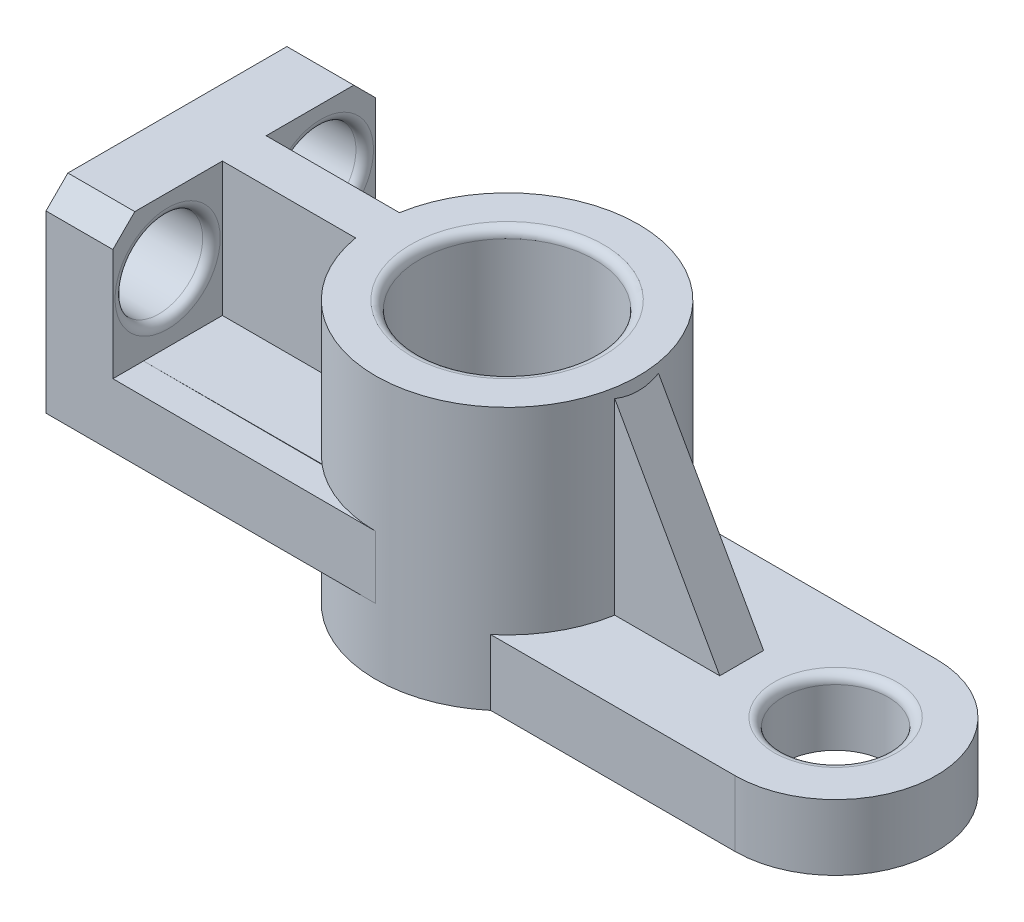
SolidWorks part; units mm, degrees
ref_plane "Front Plane" through (0, 0, 0) normal (0, 0, 1) x (1, 0, 0)
ref_plane "Top Plane" through (0, 0, 0) normal (0, 1, 0) x (1, 0, 0)
ref_plane "Right Plane" through (0, 0, 0) normal (1, 0, 0) x (0, 0, -1)
sketch "Sketch1" plane through (0, 0, 0) normal (0, 1, 0) x (1, 0, 0)
  circle A0 centre (0, 14.6047) radius 30
  circle A1 centre (0, 14.6047) radius 20
  dimension "D1" = 60
extrude "Boss-Extrude1" add sketch "Sketch1" along normal blind 60
fillet "Fillet1" radius 2 1 edges at (0, 60, 5.3953)
sketch "Sketch2" plane through (0, 0, 0) normal (0, 1, 0) x (1, 0, 0)
  line L0 (19.2614, 37.6047) -> (19.2614, -8.3953)
  line L1 (19.2614, 14.6047) -> (75, 14.6047) construction
  line L2 (19.2614, 37.6047) -> (75, 37.6047)
  line L3 (19.2614, -8.3953) -> (75, -8.3953)
  line L4 (0, 44.6047) -> (0, -15.3953) construction
  circle A0 centre (0, 14.6047) radius 30 construction
  arc A1 (19.2614, 37.6047) -> (19.2614, -8.3953) centre (19.2614, 14.6047) ccw
  arc A2 (75, -8.3953) -> (75, 37.6047) centre (75, 14.6047) ccw
  circle A3 centre (75, 14.6047) radius 12
  point P6 (47.1307, 14.6047)
  dimension "D3" = 75
  dimension "D2" = 23
  dimension "D1" = 46
extrude "Boss-Extrude2" add sketch "Sketch2" along normal blind 15
sketch "Sketch3" plane through (0, 0, 8.3953) normal (0, 0, 1) x (1, 0, 0)
  line L0 (19.2614, 0) -> (19.2614, 15)
  line L1 (0, 15) -> (-60, 15)
  line L2 (0, 15) -> (0, 29.461)
  line L3 (0, 29.461) -> (-60, 29.461)
  line L4 (-60, 29.461) -> (-60, 15)
  dimension "D1" = 60
extrude "Boss-Extrude3" add sketch "Sketch3" against normal blind 46 contours L3 L4 L1 L2
sketch "Sketch4" plane through (0, 0, 8.3953) normal (0, 0, 1) x (1, 0, 0)
  line L0 (-60, 29.461) -> (-60, 60)
  line L1 (-60, 60) -> (-75.2694, 60)
  line L2 (-75.2694, 60) -> (-75.2694, 15)
  line L3 (-75.2694, 15) -> (-60, 15)
  line L4 (-60, 29.461) -> (-60, 15)
  dimension "D1" = 45
extrude "Boss-Extrude4" add sketch "Sketch4" against normal blind 46
sketch "Sketch5" plane through (0, 60, 0) normal (0, 1, 0) x (1, 0, 0)
  line L0 (-30, 14.6047) -> (-60, 14.6047) construction
  line L2 (-60, 37.6047) -> (-60, -8.3953) construction
  line L4 (-29.5804, 9.6047) -> (-60, 9.6047)
  line L5 (-29.5804, 9.6047) -> (-29.5804, 19.6047)
  line L6 (-29.5804, 19.6047) -> (-60, 19.6047)
  line L7 (-60, 9.6047) -> (-60, 19.6047)
  circle A1 centre (0, 14.6047) radius 30 construction
  dimension "D1" = 5
  dimension "D2" = 5
extrude "Boss-Extrude5" add sketch "Sketch5" against normal blind 40
sketch "Sketch9" plane through (0, 0, 8.3953) normal (0, 0, 1) x (1, 0, 0)
  line L0 (-60, 60) -> (-75.2694, 60)
  line L1 (-75.2694, 60) -> (-75.2694, 15)
  line L2 (-75.2694, 15) -> (0, 15)
  line L3 (0, 15) -> (0, 29.299)
  line L4 (0, 29.299) -> (-60, 29.461)
  line L5 (-60, 29.461) -> (-60, 60)
extrude "Boss-Extrude6" add sketch "Sketch9" along normal blind 7
sketch "Sketch11" plane through (0, 0, -37.6047) normal (0, 0, -1) x (-1, 0, 0)
  line L1 (19.2614, 15) -> (75.2694, 15)
  line L2 (75.2694, 15) -> (75.2694, 60)
  line L3 (75.2694, 60) -> (60, 60)
  line L4 (60, 60) -> (60, 29.461)
  line L5 (60, 29.461) -> (19.2614, 29.461)
  line L6 (0, 15) -> (19.2614, 15)
  line L7 (19.2614, 29.461) -> (0, 29.461)
  line L8 (0, 15) -> (0, 29.461)
extrude "Boss-Extrude7" add sketch "Sketch11" along normal blind 7
sketch "Sketch13" plane through (-60, 0, 0) normal (1, 0, 0) x (0, 0, -1)
  line L0 (-15.3953, 29.461) -> (-15.3953, 60) construction
  line L1 (9.6047, 60) -> (-15.3953, 60) construction
  line L2 (44.6047, 60) -> (44.6047, 29.461) construction
  line L3 (44.6047, 60) -> (19.6047, 60) construction
  circle A0 centre (-2.8953, 45) radius 10
  circle A1 centre (32.1047, 45) radius 10
  point P10 (0, 0)
  point P12 (32.3999, 46.5041)
  dimension "D1" = 12.5
  dimension "D3" = 12.5
  dimension "D2" = 15
  dimension "D4" = 15
extrude "Cut-Extrude1" cut sketch "Sketch13" against normal through all
chamfer "Chamfer3" distance 5 angle 45 2 edges at (-67.6347, 60, -44.6047) (-67.6347, 60, 15.3953)
fillet "Fillet2" radius 2 3 edges at (-60, 45, -7.1047) (-60, 45, -42.1047) (75, 15, -2.6047)
ref_plane "Plane1" through (0, 0, -14.6047) normal (0, 0, 1) x (1, 0, 0)
sketch "Sketch14" plane through (0, 0, -14.6047) normal (0, 0, 1) x (1, 0, 0)
  line L0 (28.3567, 60) -> (53.5567, 15)
  line L1 (30, 60) -> (-29.5804, 60) construction
  line L2 (19.2614, 15) -> (75, 15) construction
  line L3 (53.5567, 15) -> (28.3567, 15)
  line L4 (28.3567, 15) -> (28.3567, 60)
  dimension "D1" = 25.2
extrude "Boss-Extrude8" add sketch "Sketch14" along normal mid plane 10
sketch "Sketch15" plane through (0, 29.461, 0) normal (0, 1, 0) x (1, 0, 0)
  line L0 (0, 34.6047) -> (0, -5.3953)
  arc A0 (0, -5.3953) -> (0, 34.6047) centre (0, 14.6047) cw
extrude "Cut-Extrude2" cut sketch "Sketch15" against normal through all
